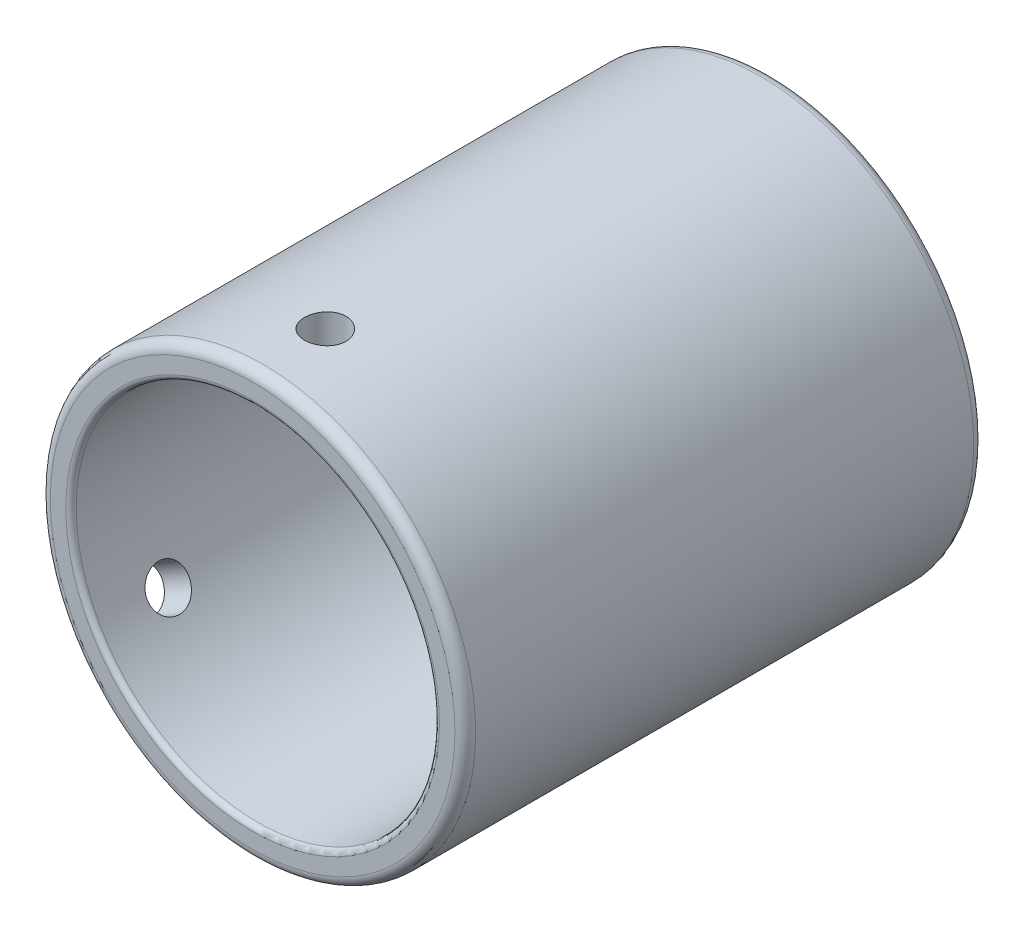
SolidWorks part; units mm, degrees
ref_plane "Front Plane" through (0, 0, 0) normal (0, 0, 1) x (1, 0, 0)
ref_plane "Top Plane" through (0, 0, 0) normal (0, 1, 0) x (1, 0, 0)
ref_plane "Right Plane" through (0, 0, 0) normal (1, 0, 0) x (0, 0, -1)
sketch "Sketch1" plane through (0, 0, 0) normal (0, 0, 1) x (1, 0, 0)
  circle A0 centre (0, 0) radius 20.5
  circle A1 centre (0, 0) radius 17.5
  dimension "D1" = 41
  dimension "D2" = 3
extrude "Boss-Extrude1" add sketch "Sketch1" along normal blind 30 and the other way blind 20
ref_plane "Plane1" through (0, 0, 23) normal (0, 0, 1) x (1, 0, 0)
sketch "Sketch2" plane through (0, 0, 23) normal (0, 0, 1) x (1, 0, 0)
  line L0 (0, 0) -> (0, 25.4524) construction
sketch "Sketch3" plane through (0, 0, 0) normal (0, 1, 0) x (1, 0, 0)
  line L0 (0, -25.2738) -> (0, 25.2738) construction
  line L1 (-22.55, -23) -> (22.55, -23) construction
  circle A0 centre (0, -23) radius 2
  dimension "D1" = 4
extrude "Cut-Extrude1" cut sketch "Sketch3" along normal through all
pattern_circular "CirPattern1" count 2 over 120 about axis through (0, 0, -20) along (0, 0, 1) of "Cut-Extrude1"
fillet "Fillet1" radius 1 2 edges at (20.5, 0, -20) (20.5, 0, 30)
fillet "Fillet2" radius 0.5 2 edges at (17.5, 0, -20) (17.5, 0, 30)
